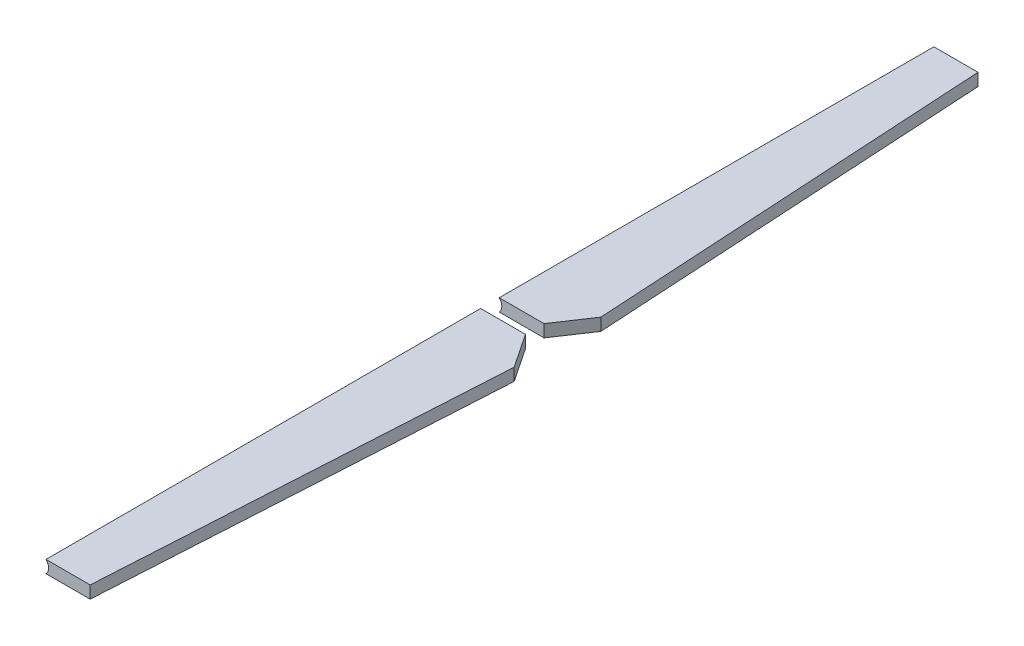
SolidWorks part; units mm, degrees
ref_plane "Front Plane" through (0, 0, 0) normal (0, 0, 1) x (1, 0, 0)
ref_plane "Top Plane" through (0, 0, 0) normal (0, 1, 0) x (1, 0, 0)
ref_plane "Right Plane" through (0, 0, 0) normal (1, 0, 0) x (0, 0, -1)
sketch "Sketch1" plane through (0, 0, 0) normal (0, 1, 0) x (1, 0, 0)
  line L0 (0, 497.2644) -> (0, 7.5) construction
  line L6 (47.8, 150.7317) -> (0, 150.7317) construction
  line L7 (0, 7.5) -> (0, -7.5) construction
  line L11 (0, -358.35) -> (0, -497.2644) construction
  line L14 (35.6506, -358.35) -> (0, -358.35)
  line L15 (54.5725, -34.9979) -> (35.6506, -358.35)
  line L16 (54.5725, -34.9979) -> (36.206, -7.5)
  line L17 (0, -7.5) -> (20.1804, -7.5)
  line L18 (0, -358.35) -> (0, -7.5)
  line L20 (20.1804, -7.5) -> (36.206, -7.5)
  line L21 (0, 0) -> (87.6609, 0) construction
  point P4 (0, 0)
  point P7 (0, 182.925)
  dimension "D2" = 47.8
  dimension "D4" = 7.5
extrude "Boss-Extrude1" add sketch "Sketch1" along normal blind 10
sketch "Sketch2" plane through (0, 0, 358.35) normal (0, 0, 1) x (1, 0, 0)
  line L0 (0, 10) -> (0, 0)
  arc A0 (0, 10) -> (0, 0) centre (-5, 5) cw
extrude "Cut-Extrude1" cut sketch "Sketch2" against normal through all
scale "Scale3" scale about centroid uniform scaling yes scale factor 0.6
ref_plane "Plane1" through (0, 0, 68.8674) normal (0, 0, -1) x (-1, 0, 0)
mirror "Mirror3" about plane through (0, 0, 68.8674) normal (0, 0, -1) of bodies 111
